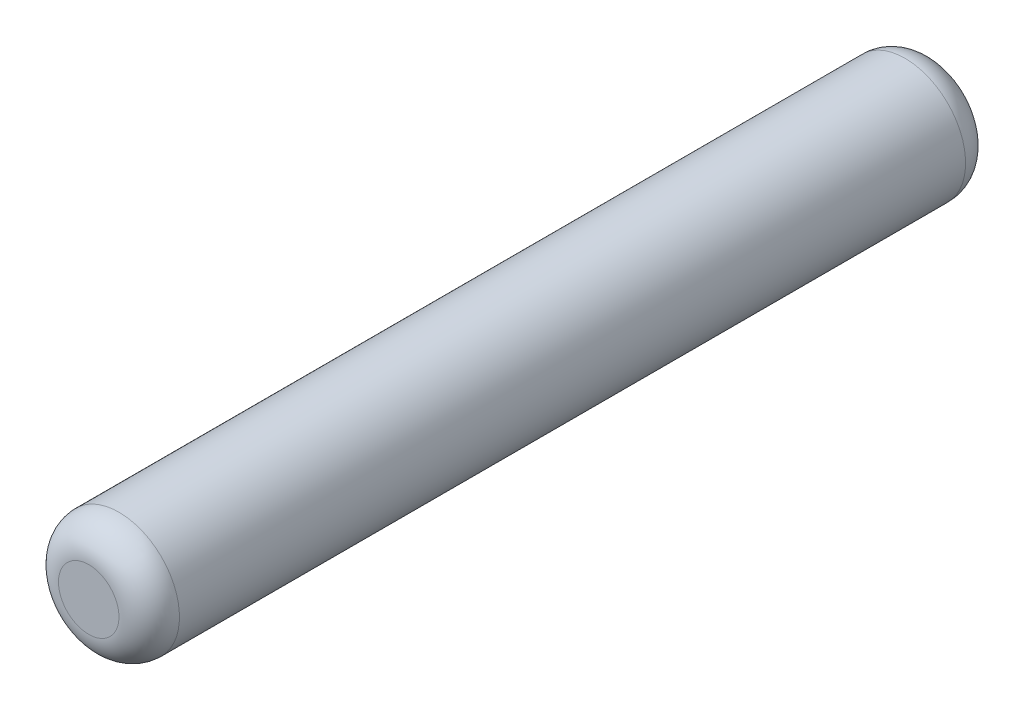
SolidWorks part; units mm, degrees
ref_plane "Front Plane" through (0, 0, 0) normal (0, 0, 1) x (1, 0, 0)
ref_plane "Top Plane" through (0, 0, 0) normal (0, 1, 0) x (1, 0, 0)
ref_plane "Right Plane" through (0, 0, 0) normal (1, 0, 0) x (0, 0, -1)
ref_plane "Plane1" through (0, 0, 0) normal (0, -1, 0) x (1, 0, 0)
sketch "Sketch1" plane through (0, 0, 0) normal (0, -1, 0) x (1, 0, 0)
  line L0 (1, 14) -> (0, 14)
  line L1 (0, 14) -> (0, -14)
  line L2 (0, -14) -> (1, -14)
  line L3 (2, -13) -> (2, 13)
  line L4 (0, 14) -> (0, -14) construction
  arc A0 (1, -14) -> (2, -13) centre (1, -13) ccw
  arc A1 (2, 13) -> (1, 14) centre (1, 13) ccw
revolve "Revolve1" add sketch "Sketch1" angle 360 about L4
